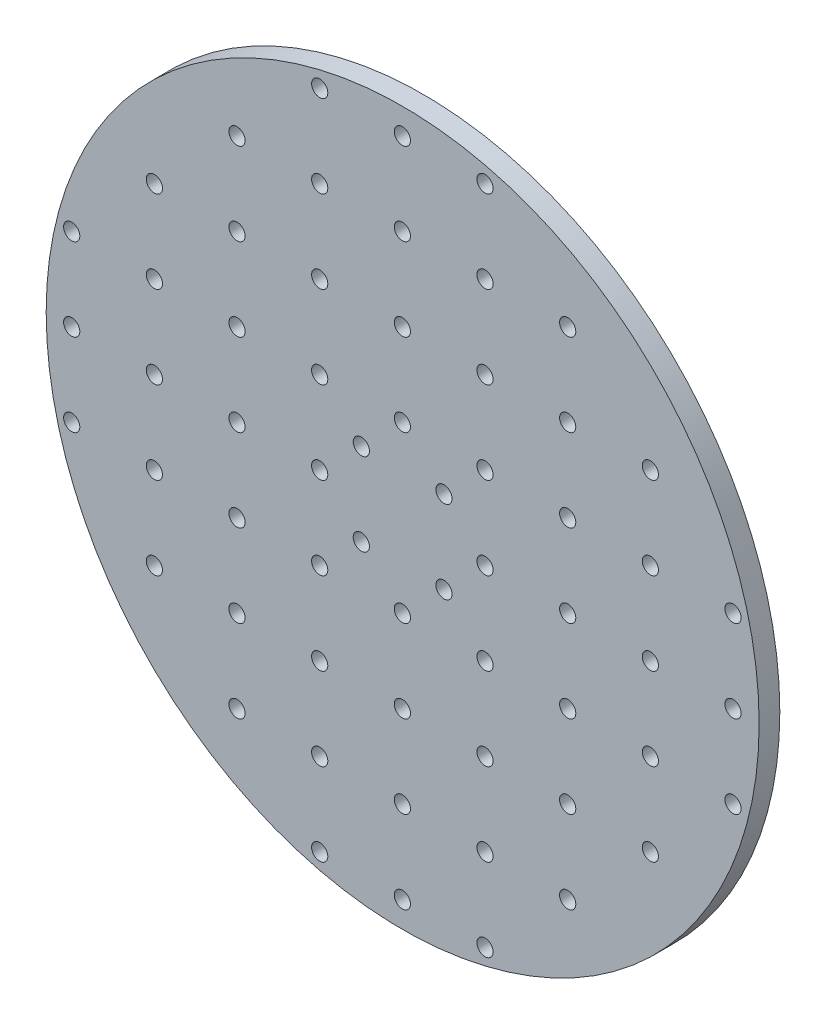
SolidWorks part; units mm, degrees
ref_plane "Front Plane" through (0, 0, 0) normal (0, 0, 1) x (1, 0, 0)
ref_plane "Top Plane" through (0, 0, 0) normal (0, 1, 0) x (1, 0, 0)
ref_plane "Right Plane" through (0, 0, 0) normal (1, 0, 0) x (0, 0, -1)
sketch "Sketch1" plane through (0, 0, 0) normal (0, 0, 1) x (1, 0, 0)
  line L1 (-12.7, 12.7) -> (12.7, 12.7) construction
  line L2 (-12.7, 12.7) -> (-12.7, -12.7) construction
  line L3 (-12.7, -12.7) -> (12.7, -12.7) construction
  line L4 (12.7, 12.7) -> (12.7, -12.7) construction
  line L5 (-12.7, 12.7) -> (12.7, -12.7) construction
  line L6 (-12.7, -12.7) -> (12.7, 12.7) construction
  circle A0 centre (0, 0) radius 109.5375
  circle A1 centre (0, 0) radius 26.035 construction
  circle A2 centre (-12.7, 12.7) radius 2.4892
  circle A3 centre (12.7, 12.7) radius 2.4892
  circle A4 centre (12.7, -12.7) radius 2.4892
  circle A5 centre (-12.7, -12.7) radius 2.4892
  dimension "D1" = 219.075
  dimension "D2" = 52.07
  dimension "D5" = 4.9784
  dimension "D3" = 25.4
  dimension "D4" = 25.4
extrude "Boss-Extrude1" add sketch "Sketch1" along normal blind 6.35
sketch "Sketch2" plane through (0, 0, 6.35) normal (0, 0, 1) x (1, 0, 0)
  line L0 (-1052.9219, -114.3) -> (48947.0781, -114.3) construction
  line L1 (-114.395, -1108.3121) -> (-114.395, 48891.6879) construction
  line L2 (114.3, -1023.8049) -> (114.3, 48976.1951) construction
  line L3 (-1159.2603, 114.3) -> (48840.7397, 114.3) construction
  line L4 (-101.695, -101.6) -> (-88.995, -101.6) construction
  line L5 (-101.695, -101.6) -> (-101.695, -88.9) construction
  line L6 (-101.695, -101.6) -> (-76.295, -101.6) construction
  line L7 (-101.695, -101.6) -> (-101.695, -76.2) construction
  line L8 (25.305, -76.2) -> (25.305, -101.6)
  line L9 (-101.695, -101.6) -> (-76.295, -101.6) construction
  line L10 (-101.695, -101.6) -> (-101.695, -76.2) construction
  line L11 (-60.5399, -109.5375) -> (53.5906, -109.5375) construction
  circle A1 centre (-101.695, -101.6) radius 2.4892
  circle A6 centre (-76.295, 0) radius 2.4892
  circle A7 centre (-76.295, 25.4) radius 2.4892
  circle A8 centre (-76.295, 50.8) radius 2.4892
  circle A51 centre (-0.095, -76.2) radius 2.4892
  circle A52 centre (25.305, -76.2) radius 2.4892
  circle A53 centre (50.705, -76.2) radius 2.4892
  circle A65 centre (-25.495, -50.8) radius 2.4892
  circle A66 centre (-0.095, -50.8) radius 2.4892
  circle A67 centre (25.305, -50.8) radius 2.4892
  circle A68 centre (50.705, -50.8) radius 2.4892
  circle A69 centre (76.105, -50.8) radius 2.4892
  circle A79 centre (-50.895, -25.4) radius 2.4892
  circle A80 centre (-25.495, -25.4) radius 2.4892
  circle A81 centre (-0.095, -25.4) radius 2.4892
  circle A82 centre (25.305, -25.4) radius 2.4892
  circle A83 centre (50.705, -25.4) radius 2.4892
  circle A84 centre (76.105, -25.4) radius 2.4892
  circle A85 centre (101.505, -25.4) radius 2.4892
  circle A94 centre (-50.895, 0) radius 2.4892
  circle A95 centre (-25.495, 0) radius 2.4892
  circle A96 centre (-0.095, 0) radius 2.4892
  circle A97 centre (25.305, 0) radius 2.4892
  circle A98 centre (50.705, 0) radius 2.4892
  circle A99 centre (76.105, 0) radius 2.4892
  circle A100 centre (101.505, 0) radius 2.4892
  circle A109 centre (-50.895, 25.4) radius 2.4892
  circle A110 centre (-25.495, 25.4) radius 2.4892
  circle A111 centre (-0.095, 25.4) radius 2.4892
  circle A112 centre (25.305, 25.4) radius 2.4892
  circle A113 centre (50.705, 25.4) radius 2.4892
  circle A114 centre (76.105, 25.4) radius 2.4892
  circle A115 centre (101.505, 25.4) radius 2.4892
  circle A124 centre (-50.895, 50.8) radius 2.4892
  circle A125 centre (-25.495, 50.8) radius 2.4892
  circle A126 centre (-0.095, 50.8) radius 2.4892
  circle A127 centre (25.305, 50.8) radius 2.4892
  circle A128 centre (50.705, 50.8) radius 2.4892
  circle A129 centre (76.105, 50.8) radius 2.4892
  circle A139 centre (-50.895, 76.2) radius 2.4892
  circle A140 centre (-25.495, 76.2) radius 2.4892
  circle A141 centre (-0.095, 76.2) radius 2.4892
  circle A142 centre (25.305, 76.2) radius 2.4892
  circle A143 centre (50.705, 76.2) radius 2.4892
  circle A155 centre (-25.495, 101.6) radius 2.4892
  circle A156 centre (-0.095, 101.6) radius 2.4892
  circle A157 centre (25.305, 101.6) radius 2.4892
  circle A289 centre (0, 0) radius 109.5375 construction
  circle A292 centre (-25.495, -101.6) radius 2.4892
  circle A293 centre (-0.095, -101.6) radius 2.4892
  circle A294 centre (25.305, -101.6) radius 2.4892
  circle A302 centre (-50.895, -76.2) radius 2.4892
  circle A303 centre (-25.495, -76.2) radius 2.4892
  circle A308 centre (-76.295, -50.8) radius 2.4892
  circle A309 centre (-50.895, -50.8) radius 2.4892
  circle A312 centre (-76.295, -25.4) radius 2.4892
  circle A347 centre (-101.695, -25.4) radius 2.4892
  circle A348 centre (-101.695, 0) radius 2.4892
  circle A349 centre (-101.695, 25.4) radius 2.4892
  circle A356 centre (101.505, 101.6) radius 2.4892 [skipped]
  circle A357 centre (50.705, -101.6) radius 2.4892 [skipped]
  circle A358 centre (76.105, -101.6) radius 2.4892 [skipped]
  circle A359 centre (101.505, -101.6) radius 2.4892 [skipped]
  circle A360 centre (76.105, -76.2) radius 2.4892 [skipped]
  circle A361 centre (101.505, -76.2) radius 2.4892 [skipped]
  circle A362 centre (101.505, -50.8) radius 2.4892 [skipped]
  circle A363 centre (101.505, 50.8) radius 2.4892 [skipped]
  circle A364 centre (101.505, 76.2) radius 2.4892 [skipped]
  circle A365 centre (50.705, 101.6) radius 2.4892 [skipped]
  circle A366 centre (76.105, 101.6) radius 2.4892 [skipped]
  circle A367 centre (-76.295, -101.6) radius 2.4892 [skipped]
  circle A368 centre (-50.895, -101.6) radius 2.4892 [skipped]
  circle A369 centre (-76.295, -76.2) radius 2.4892 [skipped]
  circle A370 centre (-76.295, 76.2) radius 2.4892 [skipped]
  circle A371 centre (76.105, 76.2) radius 2.4892 [skipped]
  circle A372 centre (-76.295, 101.6) radius 2.4892 [skipped]
  circle A373 centre (-50.895, 101.6) radius 2.4892 [skipped]
  circle A374 centre (-101.695, 101.6) radius 2.4892 [skipped]
  circle A375 centre (-101.695, -76.2) radius 2.4892 [skipped]
  circle A376 centre (-101.695, -50.8) radius 2.4892 [skipped]
  circle A377 centre (-101.695, 50.8) radius 2.4892 [skipped]
  circle A378 centre (-101.695, 76.2) radius 2.4892 [skipped]
  dimension "D1" = 4.9784
  dimension "D2" = 12.7
  dimension "D3" = 12.7
  dimension "D6" = 12.7
  dimension "D7" = 12.7
  dimension "D8" = 228.6
  dimension "D9" = 228.695
  dimension "D10" = 114.3
  dimension "D11" = 114.3
  dimension "D12" = 25.4
  dimension "D13" = 25.4
  dimension "D14" = 25.4
  dimension "D15" = 25.4
  dimension "D4" = 9
  dimension "D5" = 9
extrude "Cut-Extrude1" cut sketch "Sketch2" against normal blind 6.35
